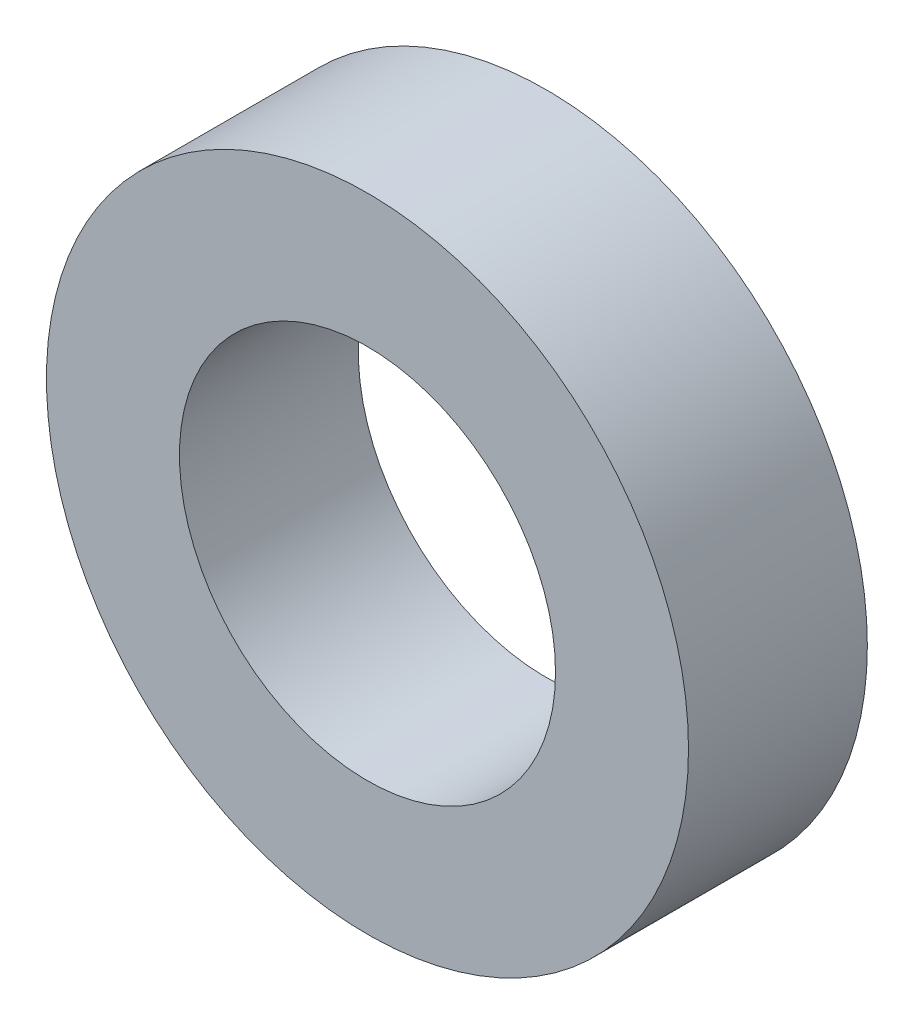
SolidWorks part; units mm, degrees
ref_plane "Front Plane" through (0, 0, 0) normal (0, 0, 1) x (1, 0, 0)
ref_plane "Top Plane" through (0, 0, 0) normal (0, 1, 0) x (1, 0, 0)
ref_plane "Right Plane" through (0, 0, 0) normal (1, 0, 0) x (0, 0, -1)
sketch "Sketch1" plane through (0, 0, 0) normal (0, 0, 1) x (1, 0, 0)
  circle A0 centre (0, 0) radius 14.224
extrude "Boss-Extrude1" add sketch "Sketch1" along normal blind 7.9248
sketch "Sketch2" plane through (0, 0, 0) normal (0, 0, 1) x (1, 0, 0)
  circle A0 centre (0, 0) radius 8.3312
extrude "Cut-Extrude1" cut sketch "Sketch2" along normal blind 7.9248
